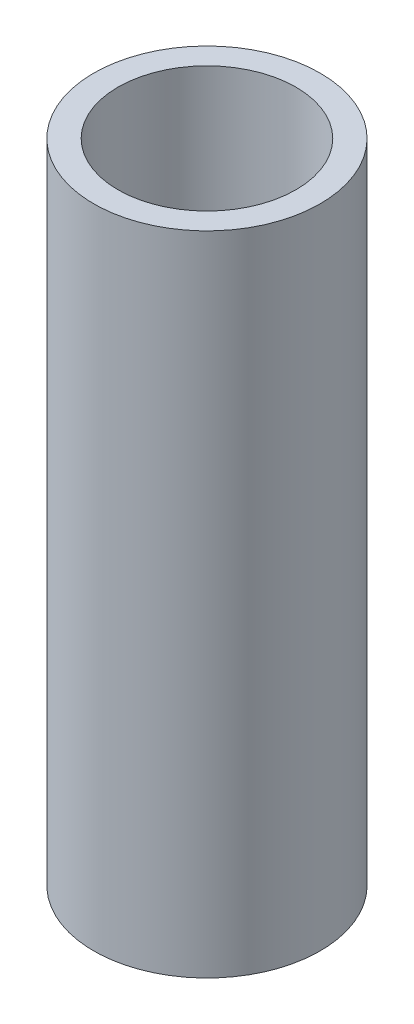
SolidWorks part; units mm, degrees
ref_plane "前视基准面" through (0, 0, 0) normal (0, 0, 1) x (1, 0, 0)
ref_plane "上视基准面" through (0, 0, 0) normal (0, 1, 0) x (1, 0, 0)
ref_plane "右视基准面" through (0, 0, 0) normal (1, 0, 0) x (0, 0, -1)
sketch "草图1" plane through (0, 0, 0) normal (1, 0, 0) x (0, 0, -1)
  line L0 (0, 0) -> (0, 93.9292) construction
  line L1 (-7, 0) -> (0, 0)
  line L3 (0, 40) -> (0, 0)
  line L27 (-7, 40) -> (0, 40)
  line L28 (-7, 0) -> (-7, 40)
  point P3 (0, 43.8356)
  point P4 (-3.5, 40)
  point P6 (0, 41.0589)
  dimension "D1" = 7
  dimension "D2" = 40
revolve "旋转4" add sketch "草图1" angle 360 about L0
sketch "草图2" plane through (0, 40, 0) normal (0, 1, 0) x (1, 0, 0)
  circle A0 centre (0, 0) radius 5.5
  dimension "D1" = 11
extrude "切除-拉伸1" cut sketch "草图2" against normal blind 35
